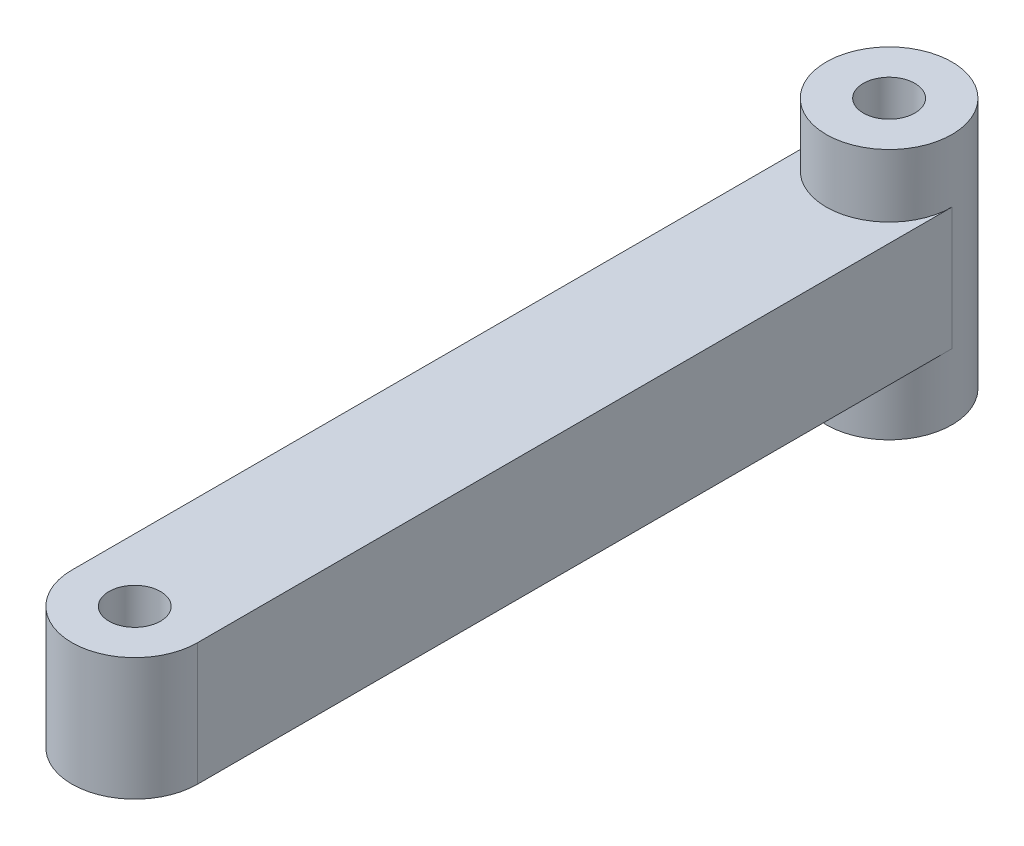
SolidWorks part; units mm, degrees
ref_plane "Plan de face" through (0, 0, 0) normal (0, 0, 1) x (1, 0, 0)
ref_plane "Plan de dessus" through (0, 0, 0) normal (0, 1, 0) x (1, 0, 0)
ref_plane "Plan de droite" through (0, 0, 0) normal (1, 0, 0) x (0, 0, -1)
sketch "Esquisse1" plane through (0, 0, 0) normal (0, 1, 0) x (1, 0, 0)
  line L0 (0, 0) -> (0, 60) construction
  line L1 (-5, 0) -> (-5, 60)
  line L2 (5, 0) -> (5, 60)
  arc A0 (-5, 0) -> (5, 0) centre (0, 0) ccw
  arc A1 (5, 60) -> (-5, 60) centre (0, 60) ccw
  circle A2 centre (0, 60) radius 2.05
  circle A3 centre (0, 0) radius 2.05
  point P3 (0, 30)
  dimension "D3" = 4.1
  dimension "D4" = 4.1
  dimension "D1" = 10
  dimension "D2" = 60
extrude "Boss.-Extru.1" add sketch "Esquisse1" along normal blind 9.75
sketch "Esquisse2" plane through (0, 9.75, 0) normal (0, 1, 0) x (1, 0, 0)
  circle A0 centre (0, 60) radius 2.05
  circle A1 centre (0, 60) radius 5
extrude "Boss.-Extru.2" add sketch "Esquisse2" along normal blind 5 and the other way blind 15
